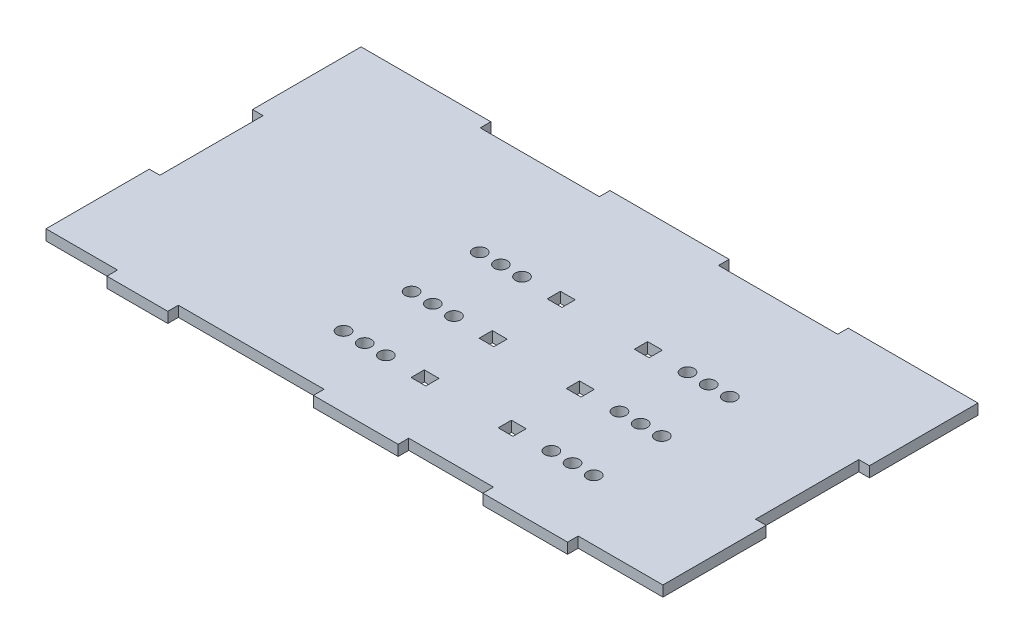
SolidWorks part; units mm, degrees
ref_plane "Front Plane" through (0, 0, 0) normal (0, 0, 1) x (1, 0, 0)
ref_plane "Top Plane" through (0, 0, 0) normal (0, 1, 0) x (1, 0, 0)
ref_plane "Right Plane" through (0, 0, 0) normal (1, 0, 0) x (0, 0, -1)
sketch "Sketch1" plane through (0, 0, 0) normal (0, 1, 0) x (1, 0, 0)
  line L1 (0, 0) -> (225, 0)
  line L2 (0, 0) -> (0, 115)
  line L3 (0, 115) -> (225, 115)
  line L4 (225, 0) -> (225, 115)
  dimension "D1" = 225
  dimension "D2" = 115
extrude "Boss-Extrude1" add sketch "Sketch1" along normal blind 4
ref_plane "Plane1" through (197.5, -108, -1) normal (0, 0, -1) x (-1, 0, 0)
sketch "Sketch3" plane through (0, 4, 0) normal (0, 1, 0) x (1, 0, 0)
  line L1 (152.09, 76.7) -> (146.51, 76.7)
  line L2 (152.09, 76.7) -> (152.09, 71.7)
  line L3 (152.09, 71.7) -> (146.51, 71.7)
  line L4 (146.51, 76.7) -> (146.51, 71.7)
  line L5 (119.17, 71.7) -> (113.59, 71.7)
  line L6 (119.17, 76.7) -> (113.59, 76.7)
  line L7 (113.59, 76.7) -> (113.59, 71.7)
  line L8 (119.17, 76.7) -> (119.17, 71.7)
  line L9 (119.17, 45.99) -> (113.59, 45.99)
  line L10 (119.17, 50.99) -> (113.59, 50.99)
  line L11 (113.59, 50.99) -> (113.59, 45.99)
  line L12 (119.17, 50.99) -> (119.17, 45.99)
  line L13 (119.17, 20.28) -> (113.59, 20.28)
  line L14 (119.17, 25.28) -> (113.59, 25.28)
  line L15 (113.59, 25.28) -> (113.59, 20.28)
  line L16 (119.17, 25.28) -> (119.17, 20.28)
  line L17 (152.09, 45.99) -> (146.51, 45.99)
  line L18 (152.09, 50.99) -> (146.51, 50.99)
  line L19 (146.51, 50.99) -> (146.51, 45.99)
  line L20 (152.09, 50.99) -> (152.09, 45.99)
  line L21 (152.09, 20.28) -> (146.51, 20.28)
  line L22 (152.09, 25.28) -> (146.51, 25.28)
  line L23 (146.51, 25.28) -> (146.51, 20.28)
  line L24 (152.09, 25.28) -> (152.09, 20.28)
  line L26 (146.51, 76.7) -> (119.17, 76.7) construction
  line L29 (146.51, 50.99) -> (119.17, 50.99) construction
  line L30 (146.51, 25.28) -> (119.17, 25.28) construction
  line L31 (180.09, 25.28) -> (192.09, 25.28) construction
  line L32 (180.09, 50.99) -> (192.09, 50.99) construction
  line L33 (180.09, 76.7) -> (192.09, 76.7) construction
  line L34 (85.59, 25.28) -> (71.09, 25.28) construction
  line L35 (85.59, 50.99) -> (71.09, 50.99) construction
  line L36 (85.59, 76.7) -> (71.09, 76.7) construction
  line L42 (225, 115) -> (0, 115) construction
  circle A0 centre (180.09, 74.2) radius 2.5
  circle A1 centre (172.09, 74.2) radius 2.5
  circle A2 centre (164.09, 74.2) radius 2.5
  circle A3 centre (101.59, 74.2) radius 2.5
  circle A4 centre (93.59, 74.2) radius 2.5
  circle A5 centre (85.59, 74.2) radius 2.5
  circle A6 centre (101.59, 48.49) radius 2.5
  circle A7 centre (93.59, 48.49) radius 2.5
  circle A8 centre (85.59, 48.49) radius 2.5
  circle A9 centre (101.59, 22.78) radius 2.5
  circle A10 centre (93.59, 22.78) radius 2.5
  circle A11 centre (85.59, 22.78) radius 2.5
  circle A12 centre (180.09, 48.49) radius 2.5
  circle A13 centre (172.09, 48.49) radius 2.5
  circle A14 centre (164.09, 48.49) radius 2.5
  circle A15 centre (180.09, 22.78) radius 2.5
  circle A16 centre (172.09, 22.78) radius 2.5
  circle A17 centre (164.09, 22.78) radius 2.5
  text T0 "ODrive 3" font "Zag Bold" height 5
  text T1 "ODrive 2" font "Zag Bold" height 5
  text T2 "ODrive 1" font "Zag Bold" height 5
  text T3 "M1" font "Zag Bold" height 5
  text T4 "M1" font "Zag Bold" height 5
  text T5 "M1" font "Zag Bold" height 5
  text T6 "M0" font "Zag Bold" height 5
  text T7 "M0" font "Zag Bold" height 5
  text T8 "M0" font "Zag Bold" height 5
  point P42 (152.09, 74.2)
  point P78 (124.19, 69.99)
  dimension "D1" = 5
  dimension "D5" = 5.58
  dimension "D6" = 5
  dimension "D9" = 12
  dimension "D11" = 14.5
  dimension "D13" = 40.8
  dimension "D14" = 12
  dimension "D15" = 12
  dimension "D2" = 3
  dimension "D3" = 2
  dimension "D4" = 3
  dimension "D7" = 2
  dimension "D8" = 3
  dimension "D10" = 3
  dimension "D12" = 3
extrude "Cut-Extrude2" cut sketch "Sketch3" against normal blind 10 contours A15 | A16 | A17 | L24 L22 L23 L21 | A12 | A13 | A14 | L20 L18 L19 L17 | A0 | A1 | A2 | L1 L4 L3 L2 | L8 L6 L7 L5 | L12 L10 L11 L9 | L16 L14 L15 L13 | A9 | A10 | A11 | A8 | A7 | A6 | A3 | A4 | A5
sketch "Sketch4" plane through (0, 4, 0) normal (0, 1, 0) x (1, 0, 0)
  line L0 (0, 115) -> (0, 0) construction
  line L5 (0, 0) -> (-4, 0)
  line L6 (0, 0) -> (0, 39)
  line L7 (0, 39) -> (-4, 39)
  line L8 (-4, 0) -> (-4, 39)
  line L9 (0, 117) -> (-4, 117)
  line L10 (0, 117) -> (0, 78)
  line L11 (0, 78) -> (-4, 78)
  line L12 (-4, 117) -> (-4, 78)
  dimension "D1" = 39
  dimension "D2" = 39
  dimension "D3" = 39
  dimension "D4" = 4
extrude "Boss-Extrude2" add sketch "Sketch4" against normal blind 4
sketch "Sketch5" plane through (0, 4, 0) normal (0, 1, 0) x (1, 0, 0)
  line L0 (135, 115) -> (135, 119)
  line L1 (225, 115) -> (180, 115)
  line L2 (225, 115) -> (225, 119)
  line L3 (225, 119) -> (180, 119)
  line L4 (180, 115) -> (180, 119)
  line L5 (135, 115) -> (90, 115)
  line L6 (90, 115) -> (90, 119)
  line L7 (135, 119) -> (90, 119)
  line L8 (45, 115) -> (45, 119)
  line L9 (45, 115) -> (0, 115)
  line L10 (0, 115) -> (0, 119)
  line L11 (45, 119) -> (0, 119)
  dimension "D1" = 45
  dimension "D2" = 4
  dimension "D3" = 3
extrude "Boss-Extrude3" add sketch "Sketch5" against normal blind 4
pattern_linear "LPattern1" count 2 spacing 229 along (1, 0, 0) of "Boss-Extrude2"
sketch "Sketch6" plane through (0, 4, 0) normal (0, 1, 0) x (1, 0, 0)
  line L8 (-4, 0) -> (229, 0) construction
  line L9 (23, 0) -> (46, 0)
  line L10 (23, 0) -> (23, -4)
  line L11 (23, -4) -> (46, -4)
  line L12 (46, 0) -> (46, -4)
  dimension "D1" = 23
  dimension "D2" = 4
  dimension "D3" = 23
extrude "Boss-Extrude4" add sketch "Sketch6" against normal blind 4
sketch "Sketch7" plane through (0, 4, 0) normal (0, 1, 0) x (1, 0, 0)
  line L0 (-4, 0) -> (69, 0) construction
  line L1 (46, 0) -> (229, 0) construction
  line L2 (165, 0) -> (165, -4)
  line L3 (101, 0) -> (133, 0)
  line L4 (101, 0) -> (101, -4)
  line L5 (101, -4) -> (133, -4)
  line L6 (133, 0) -> (133, -4)
  line L7 (165, 0) -> (197, 0)
  line L8 (197, 0) -> (197, -4)
  line L9 (165, -4) -> (197, -4)
  dimension "D1" = 73
  dimension "D2" = 32
  dimension "D3" = 4
  dimension "D4" = 32
  dimension "D5" = 2
extrude "Boss-Extrude5" add sketch "Sketch7" against normal blind 4
sketch "Sketch8" plane through (0, 4, 0) normal (0, 1, 0) x (1, 0, 0)
  line L0 (-4, 117) -> (-4, 78) construction
  line L1 (0, 117) -> (-4, 117)
  line L2 (0, 117) -> (0, 119)
  line L3 (0, 119) -> (-4, 119)
  line L4 (-4, 117) -> (-4, 119)
  line L5 (45, 119) -> (0, 119) construction
  line L7 (225, 119) -> (229, 119)
  line L8 (225, 119) -> (225, 117)
  line L9 (225, 117) -> (229, 117)
  line L10 (229, 119) -> (229, 117)
extrude "Boss-Extrude6" add sketch "Sketch8" against normal blind 4
equation "\"Dikte\"= 4"
equation "\"D1@Sketch1\"=225"
equation "\"D15@Sketch3\"=\"D14@Sketch3\""
